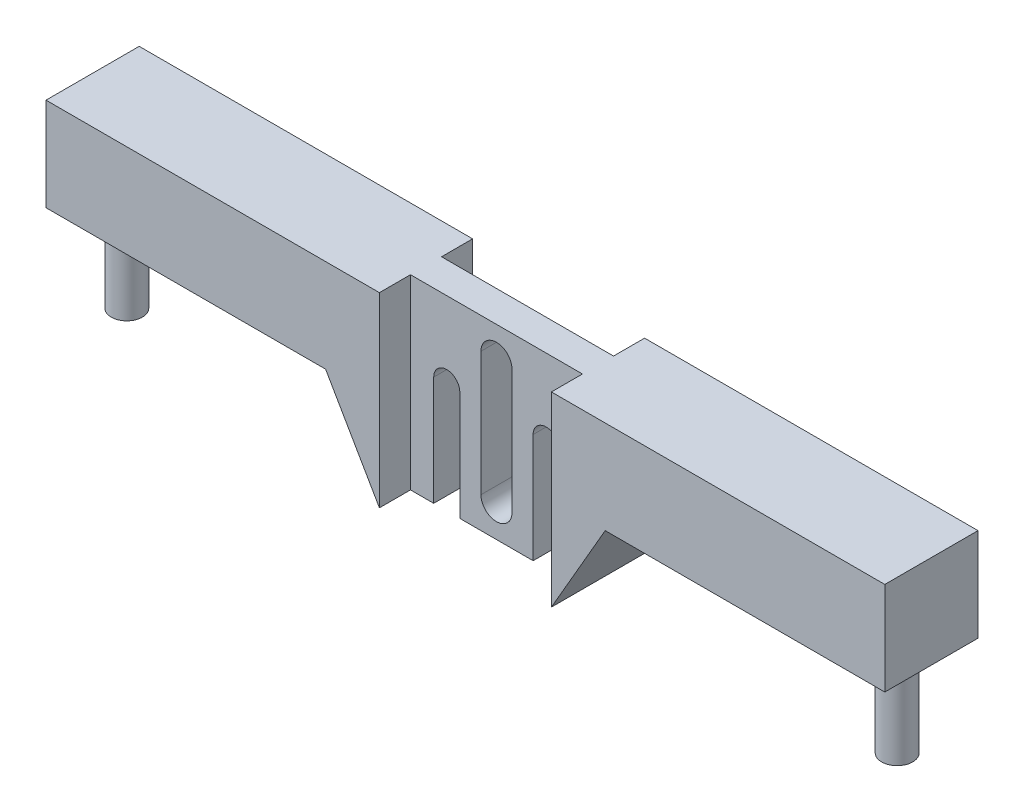
SolidWorks part; units mm, degrees
material "ABS"
ref_plane "前视基准面" through (0, 0, 0) normal (0, 0, 1) x (1, 0, 0)
ref_plane "上视基准面" through (0, 0, 0) normal (0, 1, 0) x (1, 0, 0)
ref_plane "右视基准面" through (0, 0, 0) normal (1, 0, 0) x (0, 0, -1)
sketch "Sketch1" plane through (0, 0, 0) normal (0, 0, 1) x (1, 0, 0)
  line L0 (-22.5, -7.5) -> (-13.8397, -22.5)
  line L1 (-67.5, 7.5) -> (67.5, 7.5)
  line L2 (-67.5, 7.5) -> (-67.5, -7.5)
  line L3 (-67.5, -7.5) -> (67.5, -7.5)
  line L4 (67.5, 7.5) -> (67.5, -7.5)
  line L5 (0, -7.5) -> (0, 7.5) construction
  line L6 (-67.5, 0) -> (67.5, 0) construction
  line L7 (-13.8397, -22.5) -> (13.8397, -22.5)
  line L8 (22.5, -7.5) -> (13.8397, -22.5)
  point P0 (0, 0)
  point P8 (0, -22.5)
  dimension "D1" = 135
  dimension "D2" = 15
  dimension "D3" = 15
  dimension "D4" = 45
  dimension "D5" = 60
extrude "Boss-Extrude1" add sketch "Sketch1" along normal mid plane 15 contours L4 L1 L2 L3 | L8 L3 L0 L7
sketch "Sketch2" plane through (0, 0, 7.5) normal (0, 0, 1) x (1, 0, 0)
  line L0 (0, 2.5) -> (0, -17.5) construction
  line L1 (2.5, 2.5) -> (2.5, -17.5)
  line L2 (-2.5, 2.5) -> (-2.5, -17.5)
  line L3 (8, -4.9036) -> (8, -24.9036) construction
  line L4 (10.1, -4.9036) -> (10.1, -24.9036)
  line L5 (5.9, -4.9036) -> (5.9, -24.9036)
  line L6 (-8, -4.9036) -> (-8, -24.9036) construction
  line L7 (-5.9, -4.9036) -> (-5.9, -24.9036)
  line L8 (-10.1, -4.9036) -> (-10.1, -24.9036)
  line L9 (-67.5, 7.5) -> (67.5, 7.5) construction
  arc A0 (2.5, 2.5) -> (-2.5, 2.5) centre (0, 2.5) ccw
  arc A1 (-2.5, -17.5) -> (2.5, -17.5) centre (0, -17.5) ccw
  arc A2 (10.1, -4.9036) -> (5.9, -4.9036) centre (8, -4.9036) ccw
  arc A3 (5.9, -24.9036) -> (10.1, -24.9036) centre (8, -24.9036) ccw
  arc A4 (-5.9, -4.9036) -> (-10.1, -4.9036) centre (-8, -4.9036) ccw
  arc A5 (-10.1, -24.9036) -> (-5.9, -24.9036) centre (-8, -24.9036) ccw
  point P3 (0, -7.5)
  point P10 (8, -14.9036)
  point P17 (-8, -14.9036)
  dimension "D1" = 2.5
  dimension "D5" = 2.1
  dimension "D6" = 2.1
  dimension "D8" = 5
  dimension "D2" = 20
  dimension "D3" = 20
  dimension "D4" = 20
  dimension "D7" = 8
extrude "Cut-Extrude1" cut sketch "Sketch2" against normal up to next
sketch "Sketch4" plane through (0, -22.5, 0) normal (0, -1, 0) x (1, 0, 0)
  line L0 (-13.8397, 7.5) -> (-13.8397, 2.5)
  line L1 (-13.8397, 7.5) -> (-13.8397, -7.5) construction
  line L2 (-13.8397, 2.5) -> (13.8397, 2.5)
  line L4 (13.8397, 2.5) -> (13.8397, 7.5)
  line L5 (13.8397, 7.5) -> (-13.8397, 7.5)
  line L6 (-13.8397, -2.5) -> (-13.8397, -7.5)
  line L7 (-13.8397, -7.5) -> (13.8397, -7.5)
  line L8 (13.8397, -7.5) -> (13.8397, -2.5)
  line L9 (13.8397, -2.5) -> (-13.8397, -2.5)
  line L10 (-5.9, -7.5) -> (5.9, -7.5) construction
  dimension "D1" = 5
  dimension "D2" = 5
extrude "Cut-Extrude2" cut sketch "Sketch4" against normal up to next
sketch "Sketch5" plane through (0, 7.5, 0) normal (0, 1, 0) x (1, 0, 0)
  line L0 (0, 0) -> (-74.229, 0) construction
  line L1 (0, 0) -> (0, 8.3996) construction
  circle A0 centre (61.9942, 0) radius 2.5
  circle A1 centre (-61.9942, 0) radius 2.5
  dimension "D1" = 5
extrude "Boss-Extrude2" add sketch "Sketch5" against normal blind 15 from surface at -15 starting at face at (-45, -7.5, 0)
